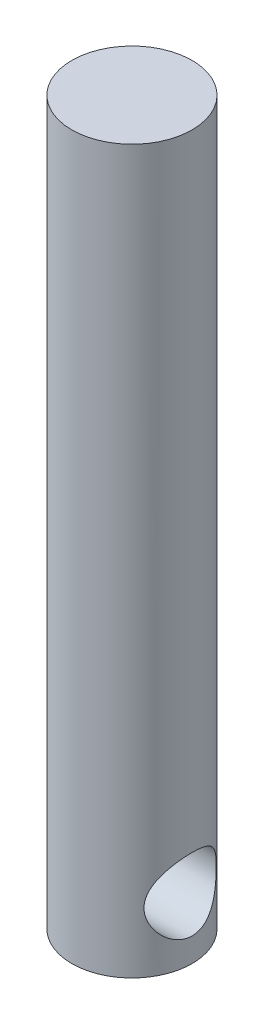
SolidWorks part; units mm, degrees
ref_plane "Front Plane" through (0, 0, 0) normal (0, 0, 1) x (1, 0, 0)
ref_plane "Top Plane" through (0, 0, 0) normal (0, 1, 0) x (1, 0, 0)
ref_plane "Right Plane" through (0, 0, 0) normal (1, 0, 0) x (0, 0, -1)
sketch "Sketch1" plane through (0, 0, 0) normal (0, 1, 0) x (1, 0, 0)
  circle A0 centre (0, 0) radius 2.5
  dimension "D1" = 5
extrude "Boss-Extrude1" add sketch "Sketch1" along normal blind 30
sketch "Sketch2" plane through (0, 0, 0) normal (1, 0, 0) x (0, 0, -1)
  circle A0 centre (0, 2.5) radius 1.5
  dimension "D1" = 3
  dimension "D2" = 2.5
extrude "Cut-Extrude1" cut sketch "Sketch2" against normal through all both and the other way through all
